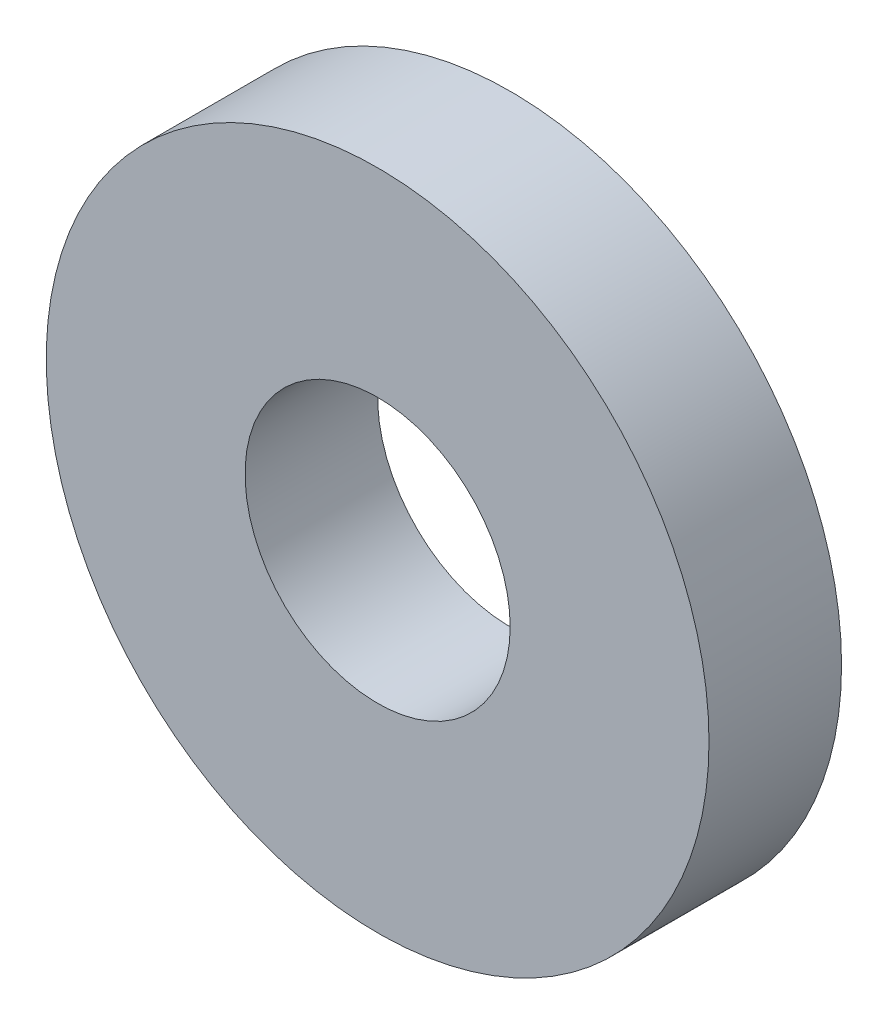
SolidWorks part; units mm, degrees
material "Алюминиевая бронза"
ref_plane "Спереди" through (0, 0, 0) normal (0, 0, 1) x (1, 0, 0)
ref_plane "Сверху" through (0, 0, 0) normal (0, 1, 0) x (1, 0, 0)
ref_plane "Справа" through (0, 0, 0) normal (1, 0, 0) x (0, 0, -1)
sketch "Эскиз1" plane through (0, 0, 0) normal (0, 0, 1) x (1, 0, 0)
  circle A1 centre (0, 0) radius 2.5
  circle A2 centre (0, 0) radius 1
  dimension "D1" = 2
  dimension "D2" = 5
extrude "Бобышка-Вытянуть1" add sketch "Эскиз1" along normal blind 1
